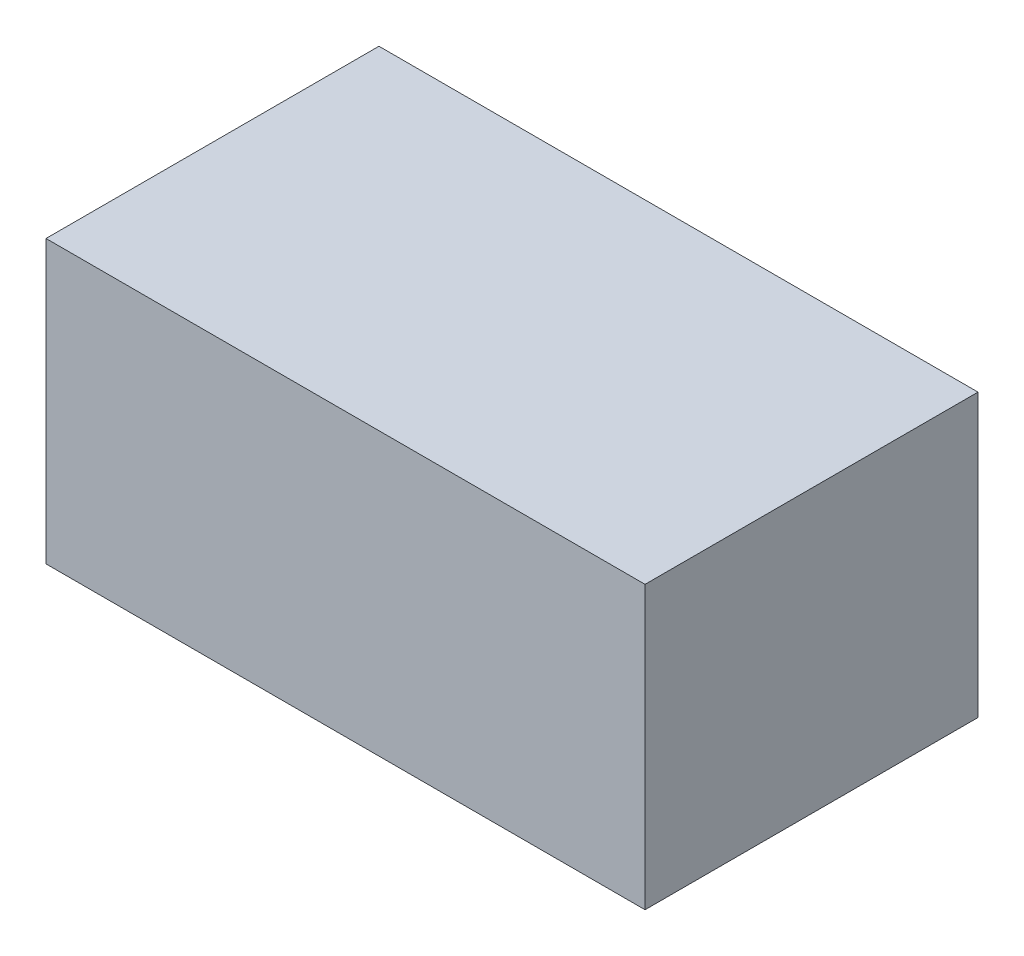
SolidWorks part; units mm, degrees
ref_plane "Front Plane" through (0, 0, 0) normal (0, 0, 1) x (1, 0, 0)
ref_plane "Top Plane" through (0, 0, 0) normal (0, 1, 0) x (1, 0, 0)
ref_plane "Right Plane" through (0, 0, 0) normal (1, 0, 0) x (0, 0, -1)
sketch "Эскиз1" plane through (0, 0, 0) normal (0, 1, 0) x (1, 0, 0)
  line L1 (-22.85, 12.7) -> (22.85, 12.7)
  line L2 (-22.85, 12.7) -> (-22.85, -12.7)
  line L3 (-22.85, -12.7) -> (22.85, -12.7)
  line L4 (22.85, 12.7) -> (22.85, -12.7)
  line L5 (-22.85, 12.7) -> (22.85, -12.7) construction
  line L6 (-22.85, -12.7) -> (22.85, 12.7) construction
  point P0 (0, 0)
  dimension "D1" = 45.7
  dimension "D2" = 25.4
extrude "Бобышка-Вытянуть1" add sketch "Эскиз1" along normal blind 21.5
